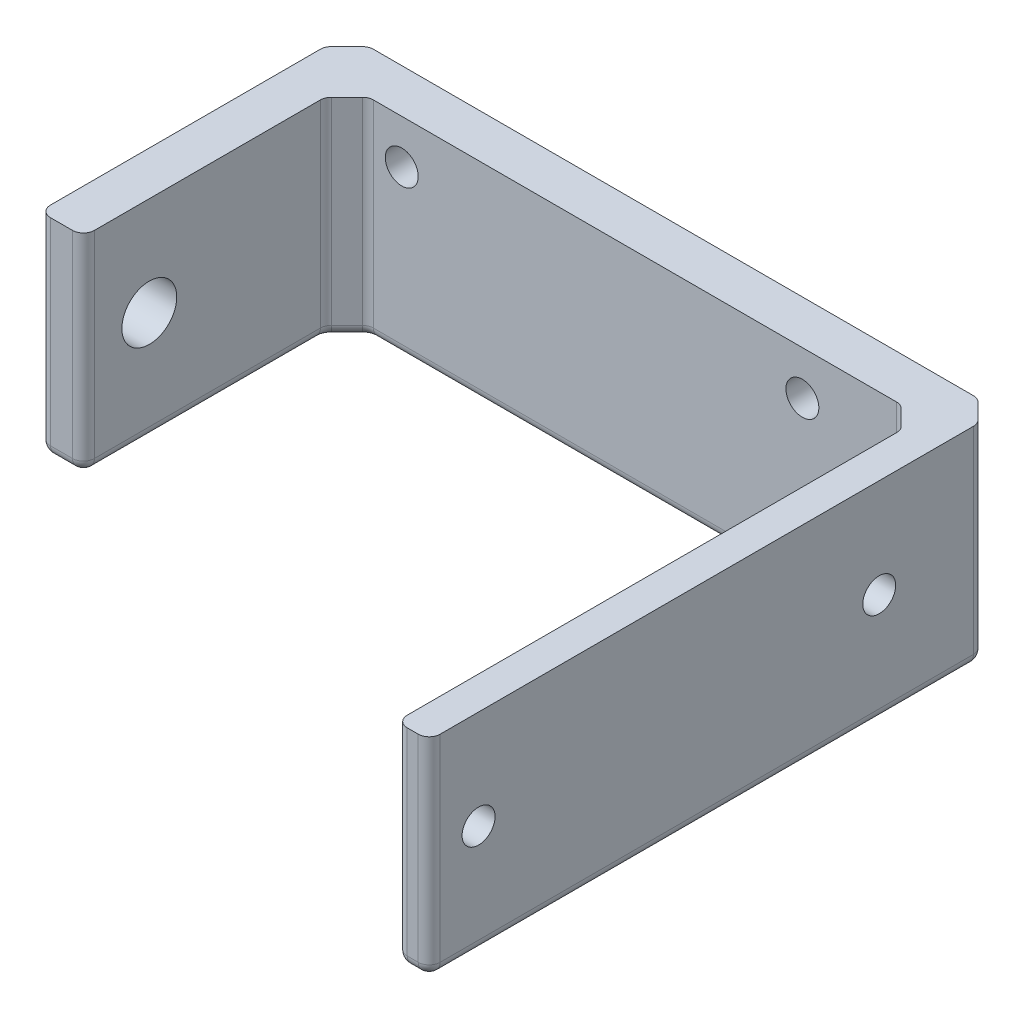
SolidWorks part; units mm, degrees
ref_plane "前视基准面" through (0, 0, 0) normal (0, 0, 1) x (1, 0, 0)
ref_plane "上视基准面" through (0, 0, 0) normal (0, 1, 0) x (1, 0, 0)
ref_plane "右视基准面" through (0, 0, 0) normal (1, 0, 0) x (0, 0, -1)
sketch "草图1" plane through (0, 0, 0) normal (0, 0, 1) x (1, 0, 0)
  line L1 (-19.2568, 5.3551) -> (40.2432, 5.3551)
  line L2 (-19.2568, 5.3551) -> (-19.2568, -13.6449)
  line L3 (-19.2568, -13.6449) -> (40.2432, -13.6449)
  line L4 (40.2432, 5.3551) -> (40.2432, -13.6449)
  line L5 (-19.2568, 5.3551) -> (40.2432, -13.6449) construction
  line L6 (-19.2568, -13.6449) -> (40.2432, 5.3551) construction
  circle A0 centre (-10.2568, 1.3551) radius 1.5
  circle A1 centre (26.2432, 1.3551) radius 1.5
  point P0 (10.4932, -4.1449)
  point P9 (0, 0)
  dimension "D1" = 9
  dimension "D7" = 3
  dimension "D8" = 3
  dimension "D2" = 14
  dimension "D3" = 4
  dimension "D4" = 4
  dimension "D5" = 15
  dimension "D6" = 36.5
extrude "凸台-拉伸1" add sketch "草图1" along normal blind 4
sketch "草图2" plane through (0, 0, 4) normal (0, 0, 1) x (1, 0, 0)
  line L0 (40.2432, 5.3551) -> (-19.2568, 5.3551) construction
  line L1 (36.2432, 5.3551) -> (40.2432, 5.3551)
  line L2 (36.2432, 5.3551) -> (36.2432, -13.6449)
  line L3 (36.2432, -13.6449) -> (40.2432, -13.6449)
  line L4 (40.2432, 5.3551) -> (40.2432, -13.6449)
  line L5 (-19.2568, -13.6449) -> (40.2432, -13.6449) construction
  line L6 (40.2432, -13.6449) -> (40.2432, 5.3551) construction
  line L8 (-15.2568, 5.3551) -> (-19.2568, 5.3551)
  line L9 (-15.2568, 5.3551) -> (-15.2568, -13.6449)
  line L10 (-15.2568, -13.6449) -> (-19.2568, -13.6449)
  line L11 (-19.2568, 5.3551) -> (-19.2568, -13.6449)
  point P15 (0, 0)
  point P16 (0, 0)
  dimension "D1" = 4
  dimension "D2" = 4
  dimension "D3" = 51.5
extrude "凸台-拉伸2" add sketch "草图2" along normal blind 24 contours L9 L8 L11 L10
sketch "草图3" plane through (0, 0, 4) normal (0, 0, 1) x (1, 0, 0)
  line L0 (40.2432, 5.3551) -> (-15.2568, 5.3551) construction
  line L1 (37.2432, 5.3551) -> (40.2432, 5.3551)
  line L2 (37.2432, 5.3551) -> (37.2432, -13.6449)
  line L3 (37.2432, -13.6449) -> (40.2432, -13.6449)
  line L4 (40.2432, 5.3551) -> (40.2432, -13.6449)
  dimension "D1" = 3
extrude "凸台-拉伸3" add sketch "草图3" along normal blind 48
sketch "草图4" plane through (-15.2568, 0, 0) normal (1, 0, 0) x (0, 0, -1)
  line L0 (-28, 5.3551) -> (-4, 5.3551) construction
  line L1 (-4, 5.3551) -> (-4, -13.6449) construction
  circle A0 centre (-22, -3.6449) radius 2.5
  dimension "D1" = 9
  dimension "D2" = 18
extrude "切除-拉伸1" cut sketch "草图4" against normal blind 48
sketch "草图5" plane through (37.2432, 0, 0) normal (-1, 0, 0) x (0, 0, 1)
  line L0 (4, 5.3551) -> (4, -13.6449) construction
  line L2 (52, 5.3551) -> (4, 5.3551) construction
  line L3 (52, -13.6449) -> (4, -13.6449) construction
  line L4 (52, 5.3551) -> (52, -13.6449) construction
  circle A0 centre (11, -3.6449) radius 1.5
  circle A1 centre (47.5, -3.6449) radius 1.5
  dimension "D1" = 3
  dimension "D2" = 3
  dimension "D3" = 7
  dimension "D4" = 36.5
  dimension "D5" = 9
  dimension "D6" = 9
  dimension "D7" = 10
  dimension "D8" = 4.5
extrude "切除-拉伸2" cut sketch "草图5" against normal blind 48
chamfer "倒角1" distance 2 angle 45 4 edges at (37.2432, -4.1449, 4) (-15.2568, -4.1449, 4) (40.2432, -4.1449, 0) (-19.2568, -4.1449, 0)
fillet "圆角1" radius 1 24 edges at (-18.2568, -13.6449, 1) (-19.2568, -13.6449, 15) (-17.2568, -13.6449, 28) (-15.2568, -13.6449, 17) (-14.2568, -13.6449, 5) (10.9932, -13.6449, 4) (36.2432, -13.6449, 5) (37.2432, -13.6449, 29) (38.7432, -13.6449, 52) (40.2432, -13.6449, 27) (39.2432, -13.6449, 1) (10.4932, -13.6449, 0) (40.2432, -4.1449, 52) (37.2432, -4.1449, 52) (37.2432, -4.1449, 6) (35.2432, -4.1449, 4) (38.2432, -4.1449, 0) (40.2432, -4.1449, 2) (-17.2568, -4.1449, 0) (-15.2568, -4.1449, 28) (-19.2568, -4.1449, 28) (-19.2568, -4.1449, 2) (-13.2568, -4.1449, 4) (-15.2568, -4.1449, 6)
